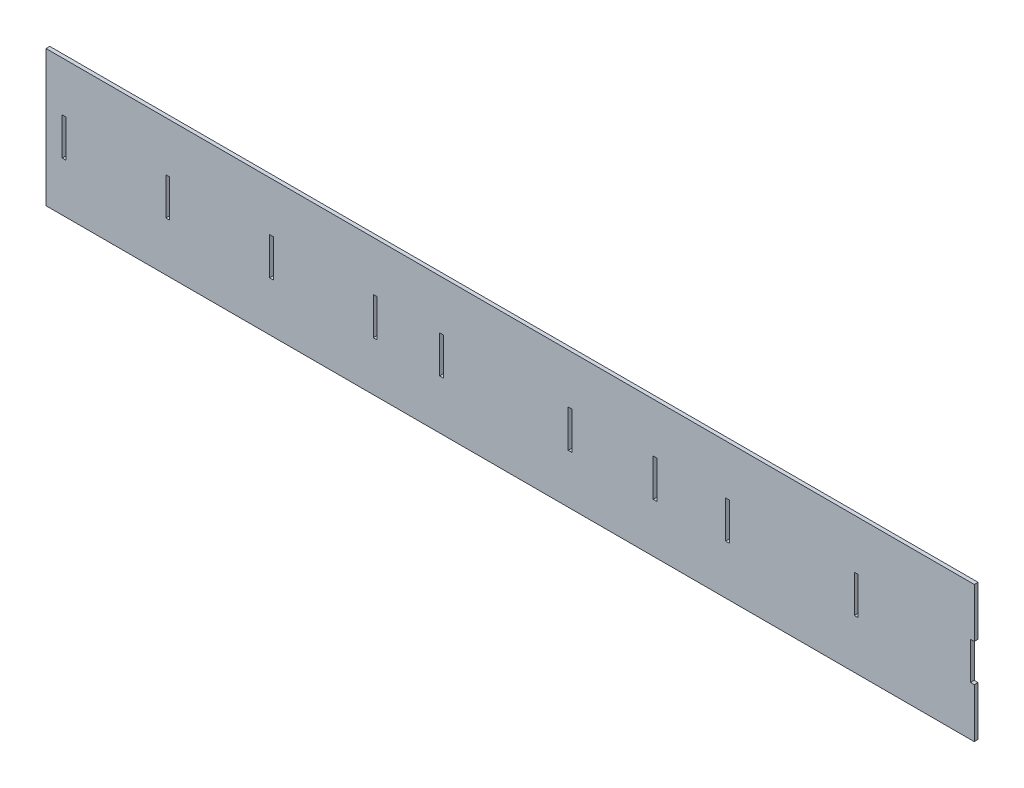
SolidWorks part; units mm, degrees
ref_plane "Front Plane" through (0, 0, 0) normal (0, 0, 1) x (1, 0, 0)
ref_plane "Top Plane" through (0, 0, 0) normal (0, 1, 0) x (1, 0, 0)
ref_plane "Right Plane" through (0, 0, 0) normal (1, 0, 0) x (0, 0, -1)
sketch "Sketch1" plane through (0, 0, 0) normal (0, 0, 1) x (1, 0, 0)
  line L1 (110.3511, 109) -> (853.3511, 109)
  line L3 (853.3511, 0) -> (110.3511, 0)
  line L4 (1244.614, 54.5) -> (110.3511, 54.5) construction
  line L5 (123.3511, 69.5) -> (126.3511, 69.5)
  line L6 (123.3511, 69.5) -> (123.3511, 39.5)
  line L7 (123.3511, 39.5) -> (126.3511, 39.5)
  line L8 (126.3511, 69.5) -> (126.3511, 39.5)
  line L14 (206.3511, 69.5) -> (209.3511, 69.5)
  line L15 (206.3511, 69.5) -> (206.3511, 39.5)
  line L16 (206.3511, 39.5) -> (209.3511, 39.5)
  line L17 (209.3511, 69.5) -> (209.3511, 39.5)
  line L18 (289.3511, 69.5) -> (292.3511, 69.5)
  line L19 (289.3511, 69.5) -> (289.3511, 39.5)
  line L20 (289.3511, 39.5) -> (292.3511, 39.5)
  line L21 (292.3511, 69.5) -> (292.3511, 39.5)
  line L22 (372.3511, 69.5) -> (375.3511, 69.5)
  line L23 (372.3511, 69.5) -> (372.3511, 39.5)
  line L24 (372.3511, 39.5) -> (375.3511, 39.5)
  line L25 (375.3511, 69.5) -> (375.3511, 39.5)
  line L26 (425.3511, 69.5) -> (428.3511, 69.5)
  line L27 (425.3511, 69.5) -> (425.3511, 39.5)
  line L28 (425.3511, 39.5) -> (428.3511, 39.5)
  line L29 (428.3511, 69.5) -> (428.3511, 39.5)
  line L30 (528.3511, 69.5) -> (531.3511, 69.5)
  line L31 (528.3511, 69.5) -> (528.3511, 39.5)
  line L32 (528.3511, 39.5) -> (531.3511, 39.5)
  line L33 (531.3511, 69.5) -> (531.3511, 39.5)
  line L34 (596.3511, 69.5) -> (599.3511, 69.5)
  line L35 (596.3511, 69.5) -> (596.3511, 39.5)
  line L36 (596.3511, 39.5) -> (599.3511, 39.5)
  line L37 (599.3511, 69.5) -> (599.3511, 39.5)
  line L38 (654.3511, 69.5) -> (657.3511, 69.5)
  line L39 (654.3511, 69.5) -> (654.3511, 39.5)
  line L40 (654.3511, 39.5) -> (657.3511, 39.5)
  line L41 (657.3511, 69.5) -> (657.3511, 39.5)
  line L42 (757.3511, 69.5) -> (760.3511, 69.5)
  line L43 (757.3511, 69.5) -> (757.3511, 39.5)
  line L44 (757.3511, 39.5) -> (760.3511, 39.5)
  line L45 (760.3511, 69.5) -> (760.3511, 39.5)
  line L46 (850.3511, 69.5) -> (853.3511, 69.5)
  line L47 (850.3511, 69.5) -> (850.3511, 39.5)
  line L48 (850.3511, 39.5) -> (853.3511, 39.5)
  line L53 (853.3511, 69.5) -> (853.3511, 109)
  line L54 (853.3511, 39.5) -> (853.3511, 0)
  line L55 (110.3511, 109) -> (110.3511, 0)
  point P2 (0, 0)
  dimension "D1" = 109
  dimension "D2" = 30
  dimension "D3" = 3
  dimension "D4" = 13
  dimension "D8" = 30
  dimension "D9" = 3
  dimension "D10" = 30
  dimension "D11" = 3
  dimension "D12" = 80
  dimension "D13" = 80
  dimension "D14" = 80
  dimension "D15" = 3
  dimension "D16" = 30
  dimension "D17" = 50
  dimension "D18" = 3
  dimension "D19" = 30
  dimension "D20" = 100
  dimension "D21" = 3
  dimension "D22" = 30
  dimension "D23" = 65
  dimension "D24" = 30
  dimension "D25" = 3
  dimension "D26" = 55
  dimension "D27" = 3
  dimension "D28" = 30
  dimension "D29" = 3
  dimension "D30" = 30
  dimension "D31" = 100
  dimension "D32" = 90
  dimension "D33" = 3
  dimension "D34" = 30
extrude "Boss-Extrude1" add sketch "Sketch1" along normal blind 3 contours L3 L1
